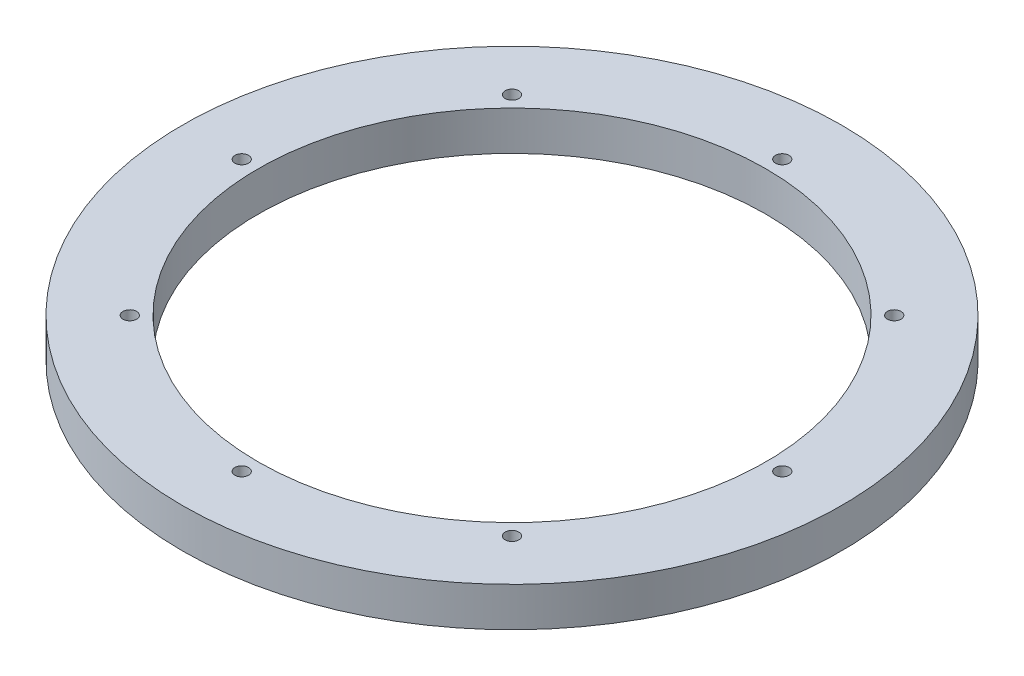
SolidWorks part; units mm, degrees
material "6061 Alloy"
ref_plane "Front Plane" through (0, 0, 0) normal (0, 0, 1) x (1, 0, 0)
ref_plane "Top Plane" through (0, 0, 0) normal (0, 1, 0) x (1, 0, 0)
ref_plane "Right Plane" through (0, 0, 0) normal (1, 0, 0) x (0, 0, -1)
sketch "Sketch1" plane through (0, 0, 0) normal (0, 1, 0) x (1, 0, 0)
  circle A0 centre (0, 0) radius 49.2125
  circle A1 centre (0, 0) radius 63.881
  circle A3 centre (0, -52.3875) radius 1.3208
  circle A4 centre (-37.0436, -37.0436) radius 1.3208
  circle A5 centre (-52.3875, 0) radius 1.3208
  circle A6 centre (-37.0436, 37.0436) radius 1.3208
  circle A7 centre (0, 52.3875) radius 1.3208
  circle A8 centre (37.0436, 37.0436) radius 1.3208
  circle A9 centre (52.3875, 0) radius 1.3208
  circle A10 centre (37.0436, -37.0436) radius 1.3208
  point P21 (0, 0)
  dimension "D1" = 98.425
  dimension "D4" = 2.6416
  dimension "D5" = 52.3875
  dimension "D2" = 14.6685
  dimension "D6" = 8
extrude "Boss-Extrude1" add sketch "Sketch1" along normal blind 7.62
equation "\"Middle Coupler Inner Daimeter\"= 3.875in"
equation "\"Middle Coupler  Wall Thickness\" = 0.25in"
equation "\"Middle Coupler Bottom Thickness\"= 0.2in"
equation "\"Bearing Rail Offset\"= 0.45in"
equation "\"3-56 UNF Tap\"= 0.089in"
equation "\"3-56 UNF Clearance\"= 0.104in"
equation "\"D5@Sketch1\"=(\"Middle Coupler Inner Daimeter\"*2+0.5)/4in"
equation "\"Ball Bearing Distance\"= 0.03in"
equation "\"D4@Sketch1\"=\"3-56 UNF Clearance\""
equation "\"D1@Sketch1\"=\"Middle Coupler Inner Daimeter\""
equation "\"TCA Outer Diameter\" = 6in"
equation "\"Interstage Aeroframe Wall Thickness\" = 0.072in"
equation "\"Compression Spring OD\"= 0.42in"
equation "\"10-24 Tap\"= 0.157in"
equation "\"10-24 Clearance\"= 0.196in"
equation "\"Lower Stage Fuselage Wall Thickness\" = 0.25in"
equation "\"6-32 Tap\" = 0.107in"
equation "\"1/4-20 Tap\" = 0.201in"
equation "\"D2@Sketch1\"=0.5875 - 10/1000"
